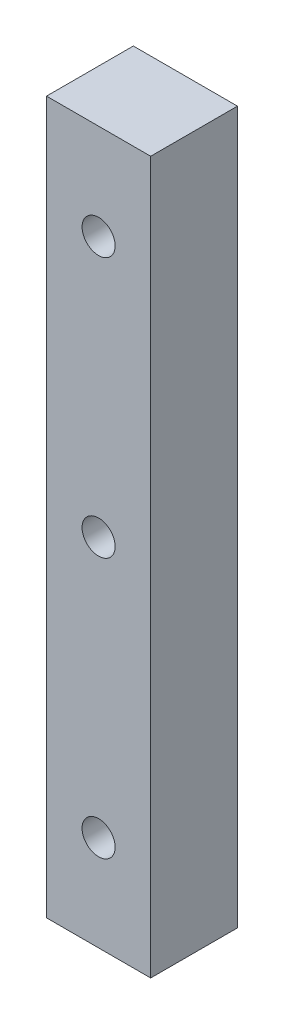
SolidWorks part; units mm, degrees
material "Wrought Stainless Steel"
ref_plane "Front Plane" through (0, 0, 0) normal (1, 0, 0) x (0, 1, 0)
ref_plane "Top Plane" through (0, 0, 0) normal (0, 0, 1) x (0, 1, 0)
ref_plane "Right Plane" through (0, 0, 0) normal (0, 1, 0) x (-1, 0, 0)
sketch "Sketch1" plane through (0, 0, 0) normal (0, 1, 0) x (-1, 0, 0)
  line L1 (0, 0) -> (30, 0)
  line L2 (0, 0) -> (0, 25)
  line L3 (0, 25) -> (30, 25)
  line L4 (30, 0) -> (30, 25)
  dimension "D1" = 30
  dimension "D2" = 25
extrude "Boss-Extrude1" add sketch "Sketch1" along normal blind 205
sketch "Sketch3" plane through (0, 0, 0) normal (0, 0, -1) x (1, 0, 0)
  line L0 (-15, 0) -> (-15, -205) construction
  line L1 (0, 0) -> (-30, 0) construction
  line L2 (0, -205) -> (-30, -205) construction
  line L3 (-30, -102.5) -> (0, -102.5) construction
  line L4 (-30, -205) -> (-30, 0) construction
  line L5 (0, -205) -> (0, 0) construction
  circle A0 centre (-15, -102.5) radius 4.7625
  circle A1 centre (-15, -27.5) radius 4.7625
  circle A2 centre (-15, -177.5) radius 4.7625
  dimension "D1" = 9.525
  dimension "D2" = 9.525
  dimension "D3" = 9.525
  dimension "D4" = 150
  dimension "D5" = 75
extrude "Cut-Extrude1" cut sketch "Sketch3" against normal up to next
equation "\"length\" = 205mm"
equation "\"base\" = 30mm"
equation "\"height\"= 25mm"
equation "\"out_hole_dist\"= 150mm"
equation "\"diameter\"= .375in"
equation "\"D1@Sketch1\"=\"base\""
equation "\"D2@Sketch1\"=\"height\""
equation "\"D1@Boss-Extrude1\"=\"length\""
equation "\"D1@Sketch3\"=\"diameter\""
equation "\"D2@Sketch3\"=\"diameter\""
equation "\"D3@Sketch3\"=\"diameter\""
equation "\"D4@Sketch3\"=\"out_hole_dist\""
equation "\"D5@Sketch3\"=\"out_hole_dist\"*.5"
